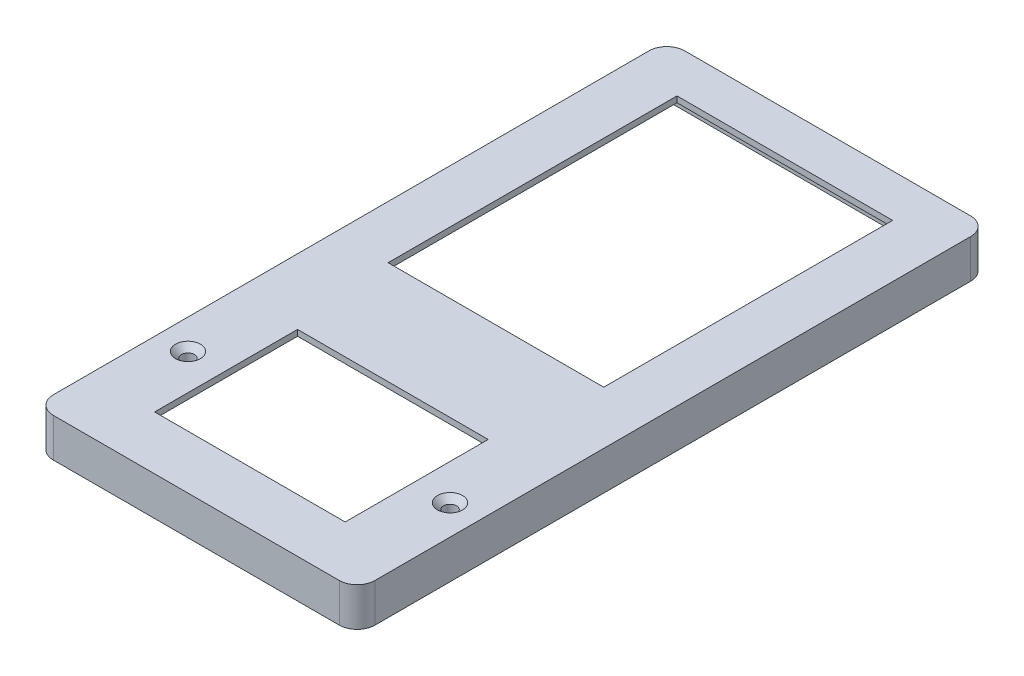
SolidWorks part; units mm, degrees
ref_plane "Front Plane" through (0, 0, 0) normal (0, 0, 1) x (1, 0, 0)
ref_plane "Top Plane" through (0, 0, 0) normal (0, 1, 0) x (1, 0, 0)
ref_plane "Right Plane" through (0, 0, 0) normal (1, 0, 0) x (0, 0, -1)
sketch "Sketch1" plane through (0, 0, 0) normal (0, 1, 0) x (1, 0, 0)
  line L0 (24.75, -50.75) -> (24.75, 50.75)
  line L1 (27, -53) -> (-27, -53)
  line L2 (27, -53) -> (27, 53)
  line L3 (27, 53) -> (-27, 53)
  line L4 (-27, -53) -> (-27, 53)
  line L5 (27, -53) -> (-27, 53) construction
  line L6 (27, 53) -> (-27, -53) construction
  line L7 (24.75, 50.75) -> (-24.75, 50.75)
  line L8 (-24.75, -50.75) -> (-24.75, 50.75)
  line L9 (24.75, -50.75) -> (-24.75, -50.75)
  point P0 (0, 0)
  dimension "D1" = 54
  dimension "D2" = 106
  dimension "D3" = 2.25
extrude "Boss-Extrude1" add sketch "Sketch1" against normal blind 5.5
sketch "Sketch2" plane through (0, 0, 0) normal (0, 1, 0) x (1, 0, 0)
  line L0 (27, 53) -> (-27, 53) construction
  line L1 (-18.1, 45.8) -> (18.1, 45.8)
  line L2 (-18.1, 45.8) -> (-18.1, -2.7)
  line L3 (-18.1, -2.7) -> (18.1, -2.7)
  line L4 (18.1, 45.8) -> (18.1, -2.7)
  line L5 (-18.1, 45.8) -> (18.1, -2.7) construction
  line L6 (-18.1, -2.7) -> (18.1, 45.8) construction
  line L7 (-27, -53) -> (27, -53) construction
  line L8 (-16, -44) -> (16, -44)
  line L9 (-16, -44) -> (-16, -20)
  line L10 (-16, -20) -> (16, -20)
  line L11 (16, -44) -> (16, -20)
  line L12 (-16, -44) -> (16, -20) construction
  line L13 (-16, -20) -> (16, -44) construction
  line L18 (-27, 53) -> (-27, -53)
  line L19 (-27, -53) -> (27, -53)
  line L20 (27, -53) -> (27, 53)
  line L21 (27, 53) -> (-27, 53)
  line L22 (-27, 53) -> (-27, -53)
  line L23 (-27, -53) -> (27, -53)
  line L24 (27, -53) -> (27, 53)
  line L25 (27, 53) -> (-27, 53)
  point P0 (0, 21.55)
  point P9 (0, -32)
  point P15 (0, -20)
  dimension "D1" = 36.2
  dimension "D2" = 48.5
  dimension "D3" = 7.2
  dimension "D4" = 33
  dimension "D5" = 9
  dimension "D6" = 32
  dimension "D7" = 0
extrude "Boss-Extrude2" add sketch "Sketch2" along normal blind 1
sketch "Sketch3" plane through (0, 0, 0) normal (0, -1, 0) x (1, 0, 0)
  line L0 (27, -53) -> (-27, -53) construction
  line L1 (21.6, 11.7715) -> (17.6, 11.7715)
  line L2 (21.6, 11.7715) -> (21.6, -48.9285)
  line L3 (21.6, -48.9285) -> (-21.6, -48.9285)
  line L4 (-21.6, 11.7715) -> (-21.6, -48.9285)
  line L5 (21.6, 11.7715) -> (-21.6, -48.9285) construction
  line L6 (21.6, -48.9285) -> (-21.6, 11.7715) construction
  line L7 (25.1, 15.2715) -> (25.1, -52.4285)
  line L8 (25.1, -52.4285) -> (-25.1, -52.4285)
  line L9 (-25.1, 15.2715) -> (-25.1, -52.4285)
  line L10 (25.1, 15.2715) -> (17.6, 15.2715)
  line L11 (17.6, 11.7715) -> (17.6, 15.2715)
  line L12 (-17.6, 11.7715) -> (-17.6, 15.2715)
  line L13 (-17.6, 11.7715) -> (-21.6, 11.7715)
  line L14 (21.6, 11.7715) -> (-21.6, 11.7715) construction
  line L15 (-17.6, 15.2715) -> (-25.1, 15.2715)
  line L16 (25.1, 15.2715) -> (-25.1, 15.2715) construction
  point P0 (0, -18.5785)
  dimension "D1" = 60.7
  dimension "D2" = 43.2
  dimension "D3" = 4.0715
  dimension "D5" = 4
  dimension "D6" = 4
  dimension "D4" = 3.5
extrude "Boss-Extrude3" add sketch "Sketch3" along normal blind 2
sketch "Sketch4" plane through (0, 0, 0) normal (0, -1, 0) x (1, 0, 0)
  line L0 (-27, -53) -> (-27, 53) construction
  line L1 (-27, 53) -> (27, 53) construction
  circle A0 centre (-22, 32.4) radius 3
  dimension "D3" = 6
  dimension "D1" = 5
  dimension "D2" = 20.6
extrude "Boss-Extrude4" add sketch "Sketch4" along normal blind 2
sketch "Sketch5" plane through (0, 0, 0) normal (0, -1, 0) x (1, 0, 0)
  circle A0 centre (-22, 32.4) radius 1.1
  dimension "D1" = 2.2
extrude "Cut-Extrude1" cut sketch "Sketch5" along normal through all both and the other way through all
mirror "Mirror1" about plane through (0, 0, 0) normal (1, 0, 0) of "Cut-Extrude1", "Boss-Extrude4"
fillet "Fillet1" radius 3 4 edges at (-27, -2.25, -53) (27, -2.25, -53) (27, -2.25, 53) (-27, -2.25, 53)
chamfer "Chamfer1" distance 1 angle 45 2 edges at (22, 1, 31.3) (-22, 1, 31.3)
sketch "Sketch6" plane through (0, -5.5, 0) normal (0, -1, 0) x (1, 0, 0)
  line L1 (-24.75, 50.75) -> (24.75, 50.75)
  line L2 (-24.75, 50.75) -> (-24.75, 51.75)
  line L3 (-24.75, 51.75) -> (24.75, 51.75)
  line L4 (24.75, 50.75) -> (24.75, 51.75)
  dimension "D1" = 1
extrude "Cut-Extrude2" cut sketch "Sketch6" against normal blind 2
